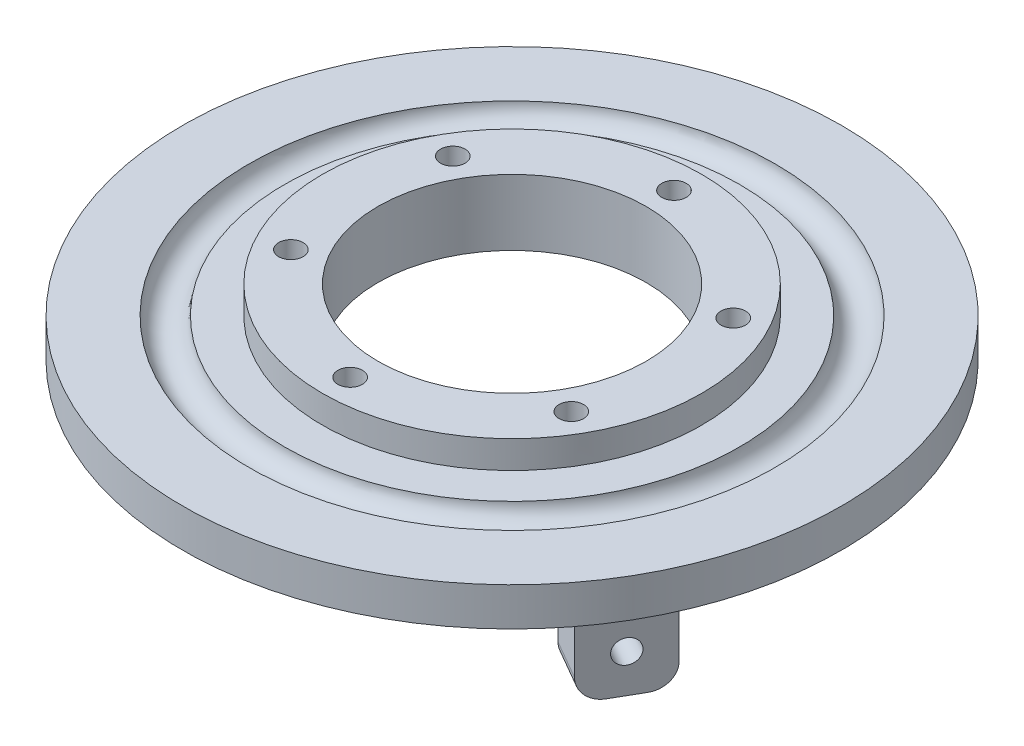
SolidWorks part; units mm, degrees
ref_plane "Front Plane" through (0, 0, 0) normal (0, 0, 1) x (1, 0, 0)
ref_plane "Top Plane" through (0, 0, 0) normal (0, 1, 0) x (1, 0, 0)
ref_plane "Right Plane" through (0, 0, 0) normal (1, 0, 0) x (0, 0, -1)
sketch "Sketch1" plane through (0, 0, 0) normal (0, 0, 1) x (1, 0, 0)
  line L0 (-34.3228, 5) -> (-43, 5)
  line L1 (0, 0) -> (-43, 0)
  line L2 (0, 0) -> (0, 5)
  line L3 (0, 5) -> (-29.6772, 5)
  line L4 (-43, 0) -> (-43, 5)
  arc A0 (-34.3228, 5) -> (-29.6772, 5) centre (-32, 5.1) ccw
  dimension "D3" = 4.65
  dimension "D1" = 43
  dimension "D2" = 5
  dimension "D4" = 0.1
  dimension "D5" = 32
revolve "Revolve1" add sketch "Sketch1" angle 360 about L2
sketch "Sketch2" plane through (0, 5, 0) normal (0, 1, 0) x (1, 0, 0)
  circle A0 centre (0, 0) radius 24.75
  dimension "D1" = 49.5
extrude "Boss-Extrude1" add sketch "Sketch2" along normal blind 3.6
sketch "Sketch3" plane through (0, 8.6, 0) normal (0, 1, 0) x (1, 0, 0)
  circle A0 centre (0, 0) radius 17.5
  dimension "D1" = 35
extrude "Cut-Extrude1" cut sketch "Sketch3" against normal through all both and the other way through all
sketch "Sketch4" plane through (0, 8.6, 0) normal (0, 1, 0) x (1, 0, 0)
  line L0 (-17.5, 0) -> (-24.75, 0) construction
  circle A0 centre (0, 0) radius 21.125 construction
  circle A1 centre (0, 0) radius 17.5 construction
  circle A2 centre (0, 0) radius 24.75 construction
  circle A3 centre (0, 21.125) radius 1.6
  circle A4 centre (18.2948, 10.5625) radius 1.6
  circle A5 centre (18.2948, -10.5625) radius 1.6
  circle A6 centre (0, -21.125) radius 1.6
  circle A7 centre (-18.2948, -10.5625) radius 1.6
  circle A8 centre (-18.2948, 10.5625) radius 1.6
  point P10 (-21.125, 0)
  point P13 (0, 0)
  point P14 (0, 0)
  point P15 (12.3173, 6.7918)
  point P26 (0, 0)
  point P27 (0, 0)
  point P28 (0, 0)
  dimension "D1" = 3.2
  dimension "D2" = 6
extrude "Cut-Extrude2" cut sketch "Sketch4" against normal through all both and the other way through all
sketch "Sketch5" plane through (0, 0, 0) normal (0, 1, 0) x (1, 0, 0)
  line L1 (-5, 35) -> (5, 35)
  line L2 (-5, 35) -> (-5, 40.9)
  line L3 (-5, 40.9) -> (5, 40.9)
  line L4 (5, 35) -> (5, 40.9)
  point P4 (0, 35)
  dimension "D1" = 5.9
  dimension "D2" = 10
  dimension "D3" = 35
extrude "Boss-Extrude2" add sketch "Sketch5" against normal blind 10
fillet "Fillet1" radius 3 2 edges at (-5, -10, -37.95) (5, -10, -37.95)
sketch "Sketch6" plane through (0, 0, 0) normal (0, 0, 1) x (1, 0, 0)
  line L0 (-2, -10) -> (2, -10) construction
  circle A0 centre (0, -5) radius 1.55
  dimension "D1" = 3.1
  dimension "D2" = 5
extrude "Cut-Extrude3" cut sketch "Sketch6" against normal through all both and the other way through all
pattern_circular "CirPattern1" count 3 over 360 about axis through (0, 0, 0) along (0, 1, 0) of "Cut-Extrude3", "Fillet1", "Boss-Extrude2"
